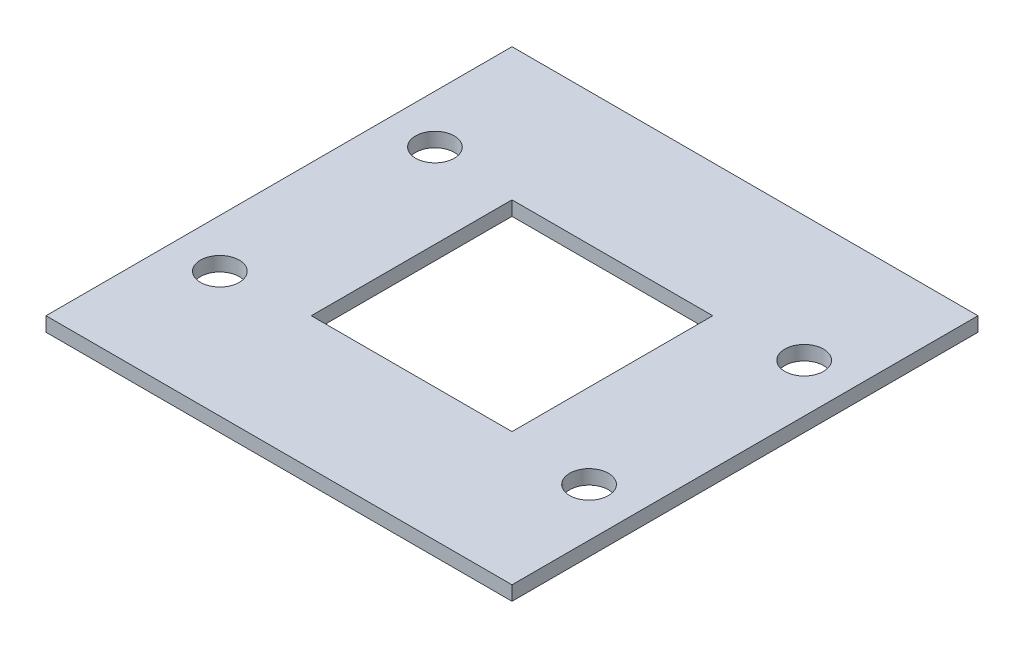
SolidWorks part; units mm, degrees
ref_plane "Alzado" through (0, 0, 0) normal (0, 0, 1) x (1, 0, 0)
ref_plane "Planta" through (0, 0, 0) normal (0, 1, 0) x (1, 0, 0)
ref_plane "Vista lateral" through (0, 0, 0) normal (1, 0, 0) x (0, 0, -1)
sketch "Croquis1" plane through (0, 0, 0) normal (0, 1, 0) x (1, 0, 0)
  line L0 (0, 0) -> (55, 55) construction
  line L1 (0, 0) -> (55, 0)
  line L2 (0, 0) -> (0, 55)
  line L3 (0, 55) -> (55, 55)
  line L4 (55, 0) -> (55, 55)
  line L5 (1.75, 0) -> (1.75, 55) construction
  line L6 (13.5, 13.5) -> (27.5, 13.5)
  line L7 (13.5, 13.5) -> (13.5, 27.5)
  line L8 (13.5, 41.5) -> (27.5, 41.5)
  line L9 (41.5, 13.5) -> (41.5, 28.15)
  line L10 (13.5, 13.5) -> (41.5, 41.5) construction
  line L11 (13.5, 41.5) -> (41.5, 13.5) construction
  line L12 (27.5, 0) -> (27.5, 55) construction
  line L13 (3.5, 0) -> (3.5, 55) construction
  line L14 (3.5, 27.5) -> (0, 27.5) construction
  line L15 (3.25, 42.5) -> (3.25, 27.5) construction
  line L16 (3.25, 27.5) -> (3.25, 12.5) construction
  line L17 (0, 27.5) -> (27.5, 27.5) construction
  line L22 (42.5, 27.5) -> (55, 27.5) construction
  line L38 (41.5, 28.15) -> (41.5, 41.5)
  line L39 (27.5, 13.5) -> (41.5, 13.5)
  line L40 (13.5, 27.5) -> (13.5, 41.5)
  line L41 (27.5, 41.5) -> (41.5, 41.5)
  circle A0 centre (1.75, 42.5) radius 1.5
  circle A1 centre (1.75, 12.5) radius 1.5
  circle A2 centre (53.25, 42.5) radius 1.5
  circle A3 centre (53.25, 12.5) radius 1.5
  point P4 (27.5, 27.5)
  point P18 (1.75, 27.5)
  point P25 (27.5, 42.5)
  point P35 (42.5, 27.5)
  dimension "D4" = 3
  dimension "D1" = 55
  dimension "D2" = 28
  dimension "D3" = 24
  dimension "D5" = 15
extrude "Saliente-Extruir1" add sketch "Croquis1" along normal blind 2
sketch "Croquis3" plane through (0, 2, 0) normal (0, 1, 0) x (1, 0, 0)
  line L0 (-5, 60) -> (-5, -5)
  line L1 (-5, -5) -> (60, -5)
  line L2 (60, -5) -> (60, 60)
  line L3 (60, 60) -> (-5, 60)
  line L4 (0, 55) -> (0, 0)
  line L5 (0, 0) -> (55, 0)
  line L6 (55, 0) -> (55, 55)
  line L7 (55, 55) -> (0, 55)
  line L8 (0, 55) -> (0, 0)
  line L9 (0, 0) -> (55, 0)
  line L10 (55, 0) -> (55, 55)
  line L11 (55, 55) -> (0, 55)
  dimension "D1" = 0
  dimension "D2" = 5
extrude "Saliente-Extruir2" add sketch "Croquis3" against normal blind 2
sketch "Croquis4" plane through (0, 2, 0) normal (0, 1, 0) x (1, 0, 0)
  circle A0 centre (53.25, 42.5) radius 2.7
  circle A1 centre (53.25, 12.5) radius 2.7
  circle A2 centre (1.75, 12.5) radius 2.7
  circle A3 centre (1.75, 42.5) radius 2.7
  dimension "D1" = 5.4
extrude "Cortar-Extruir1" cut sketch "Croquis4" against normal blind 2
